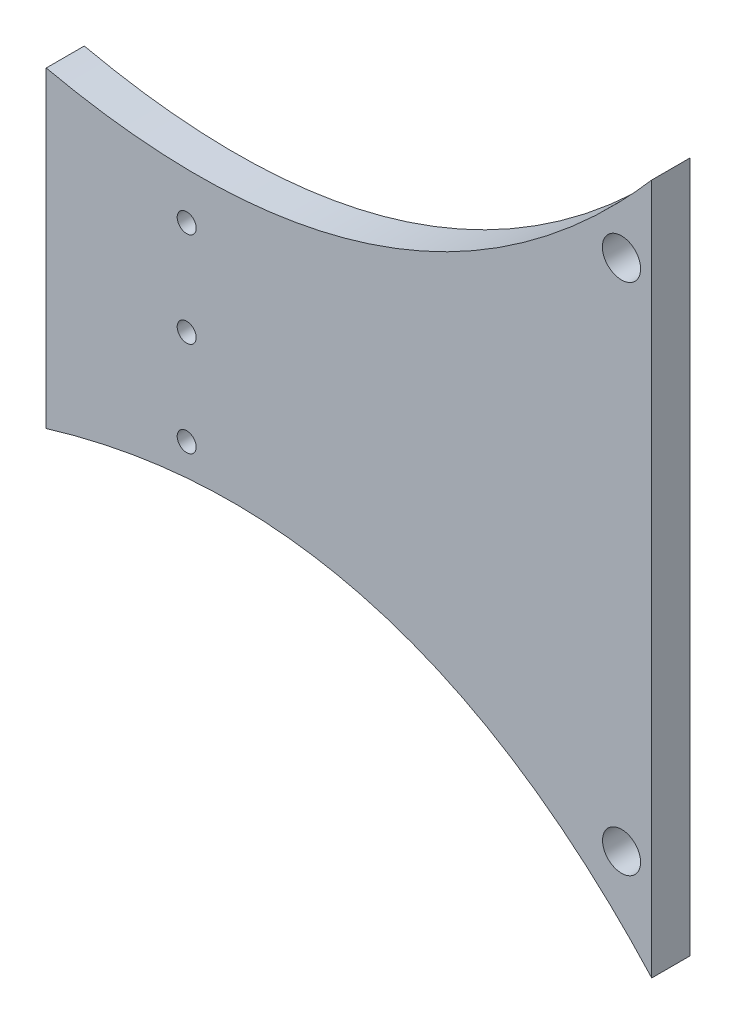
SolidWorks part; units mm, degrees
ref_plane "Front Plane" through (0, 0, 0) normal (0, 0, 1) x (1, 0, 0)
ref_plane "Top Plane" through (0, 0, 0) normal (0, 1, 0) x (1, 0, 0)
ref_plane "Right Plane" through (0, 0, 0) normal (1, 0, 0) x (0, 0, -1)
sketch "Sketch1" plane through (0, 0, 0) normal (0, 0, 1) x (1, 0, 0)
  line L0 (0, 6.7966) -> (0, 23.2034)
  line L2 (31.8163, 34.0137) -> (31.8163, -2.2971)
  line L4 (7.3821, 19.8534) -> (7.3821, 9.8896)
  circle A0 centre (7.3821, 19.8534) radius 0.5
  circle A1 centre (7.3821, 9.8896) radius 0.5
  circle A2 centre (7.3821, 14.8715) radius 0.5
  circle A3 centre (30.2271, 29.6758) radius 1.0046
  circle A4 centre (30.2303, 2.6758) radius 1
  spline S0 degree 2 poles (0, 23.2034) (18.8241, 19.0229) (31.8163, 34.0137) knots 0 0 0 1 1 1
  spline S1 degree 2 poles (0, 6.7966) (18.4732, 12.397) (31.8163, -2.2971) knots 0 0 0 1 1 1
  point P0 (30.2271, 2.6758)
  dimension "D1" = 27
  dimension "D2" = 4.9819
extrude "Boss-Extrude4" add sketch "Sketch1" along normal blind 2
